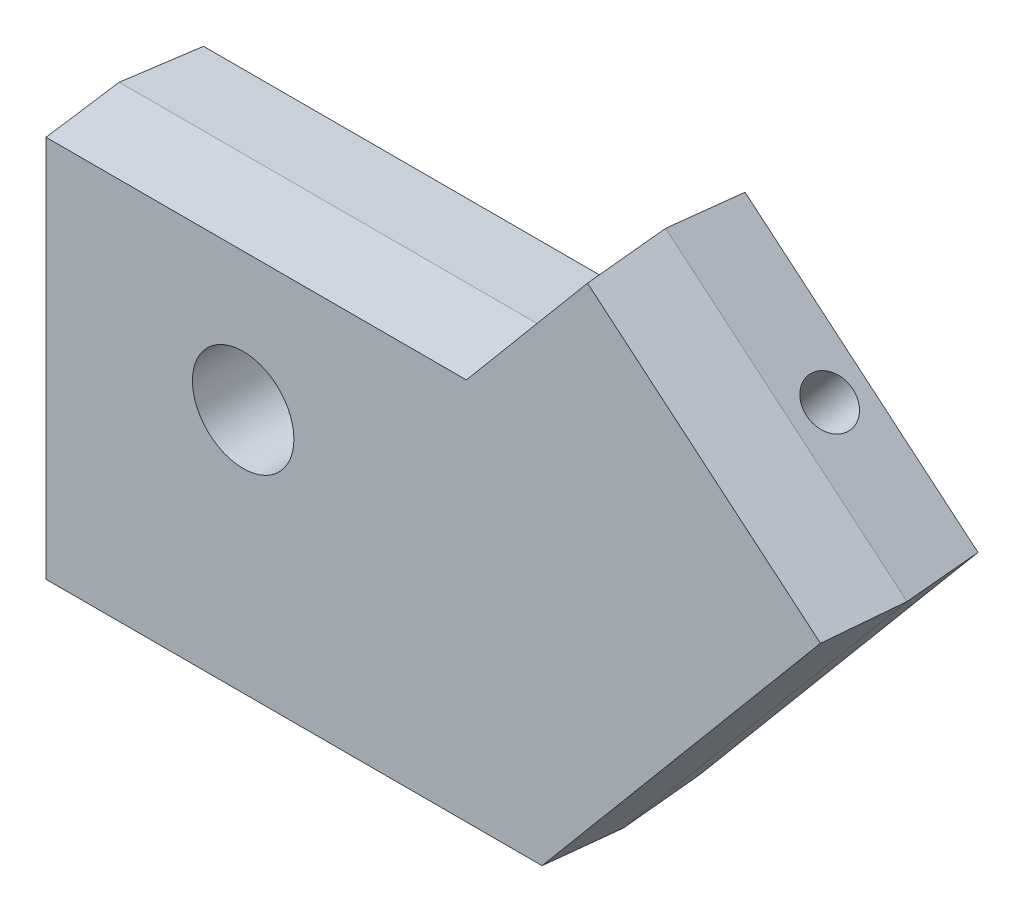
SolidWorks part; units mm, degrees
ref_plane "Front Plane" through (0, 0, 0) normal (0, 0, 1) x (1, 0, 0)
ref_plane "Top Plane" through (0, 0, 0) normal (0, 1, 0) x (1, 0, 0)
ref_plane "Right Plane" through (0, 0, 0) normal (1, 0, 0) x (0, 0, -1)
sketch "Sketch4" plane through (0, 0, 0) normal (0, 0, 1) x (1, 0, 0)
  line L6 (32, 0) -> (50, 21.4516)
  line L7 (0, 0) -> (32, 0)
  line L8 (0, 0) -> (0, 25)
  line L9 (0, 25) -> (26.8693, 25)
  line L11 (50, 21.4516) -> (34.6791, 34.3073)
  line L12 (34.6791, 34.3073) -> (26.8693, 25)
  point P1 (41.8933, 22.7789)
  point P5 (40.523, 24.1492)
  point P9 (41.5127, 0)
  point P11 (31.007, 17.1454)
  point P12 (60.9832, 47.1963)
  point P13 (75.1248, 33.0547)
  point P14 (32, 25)
  point P15 (28.2054, 25)
  point P16 (24.4782, 25)
  dimension "D1" = 20
  dimension "D2" = 25
  dimension "D3" = 32
  dimension "D4" = 130
  dimension "D5" = 50
extrude "Boss-Extrude1" add sketch "Sketch4" along normal mid plane 10 draft 4
sketch "Sketch7" plane through (0, 0, 5) normal (0, 0, 1) x (1, 0, 0)
  circle A0 centre (12.865, 15.9191) radius 3.2199
extrude "Cut-Extrude1" cut sketch "Sketch7" against normal blind 10 contours A0
sketch "Sketch9" plane through (31.0697, 37.0274, -3.38) normal (0.6412, 0.7642, -0.0698) x (0.7674, -0.6386, 0.0583)
  circle A0 centre (15.0078, 0) radius 1.5501
extrude "Cut-Extrude2" cut sketch "Sketch9" against normal blind 12
